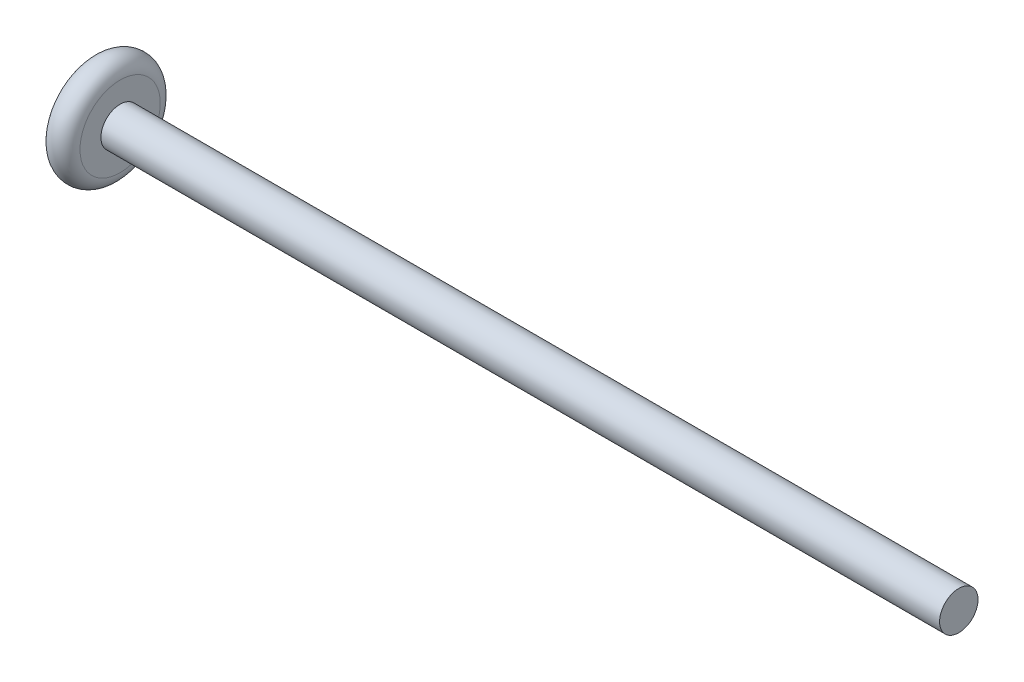
SolidWorks part; units mm, degrees
ref_plane "Ebene vorne" through (0, 0, 0) normal (0, 0, 1) x (1, 0, 0)
ref_plane "Ebene oben" through (0, 0, 0) normal (0, 1, 0) x (1, 0, 0)
ref_plane "Ebene rechts" through (0, 0, 0) normal (1, 0, 0) x (0, 0, -1)
sketch "Skizze1" plane through (0, 0, 0) normal (0, 0, 1) x (1, 0, 0)
  line L0 (0, 0) -> (112.3016, 0) construction
  line L1 (0, 0) -> (0, 4.7)
  line L2 (3.3, 4.7) -> (3.3, 2.25)
  line L3 (3.3, 2.25) -> (101.5, 2.25)
  line L4 (101.5, 2.25) -> (101.5, 0)
  line L5 (0, 0) -> (101.5, 0)
  arc A0 (0, 4.7) -> (3.3, 4.7) centre (1.65, 4.7) cw
  dimension "D1" = 3.3
  dimension "D2" = 4.7
  dimension "D3" = 2.25
  dimension "D4" = 101.5
revolve "Rotation1" add sketch "Skizze1" angle 360 about L0
